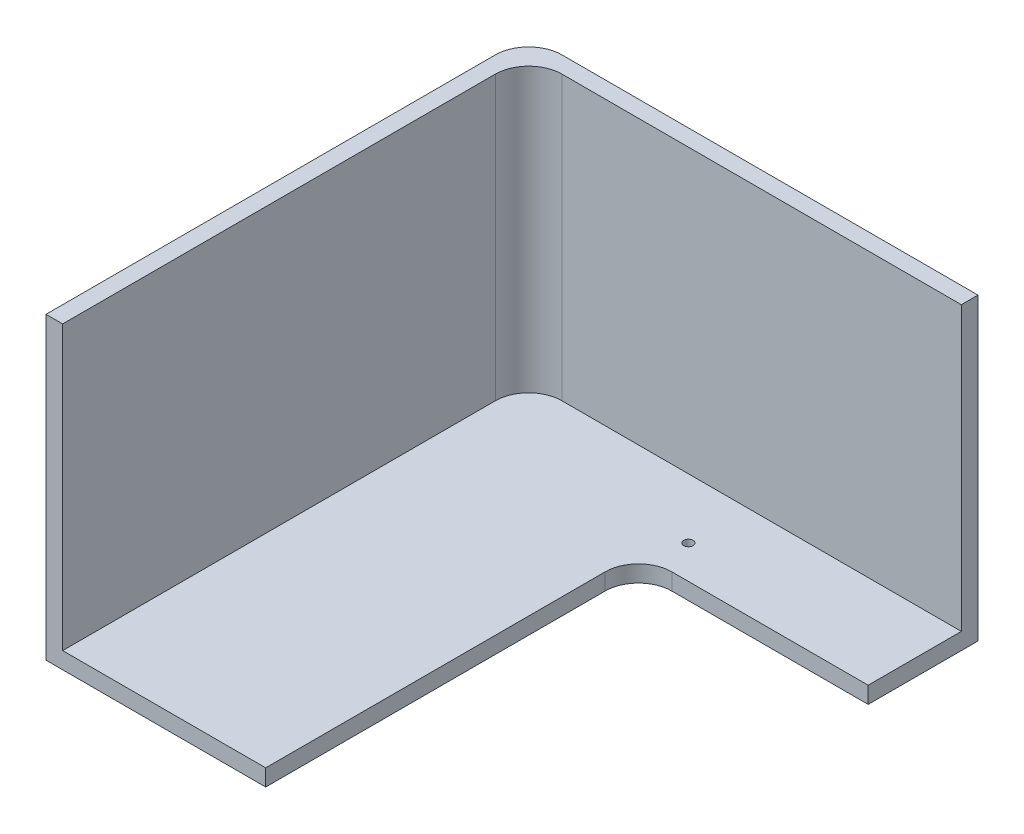
SolidWorks part; units mm, degrees
ref_plane "前视基准面" through (0, 0, 0) normal (0, 0, 1) x (1, 0, 0)
ref_plane "上视基准面" through (0, 0, 0) normal (0, 1, 0) x (1, 0, 0)
ref_plane "右视基准面" through (0, 0, 0) normal (1, 0, 0) x (0, 0, -1)
other "Configuration Table"
sketch "草图1" plane through (0, 0, 0) normal (0, 1, 0) x (1, 0, 0)
  line L1 (0, 0) -> (-135, 0)
  line L2 (0, 0) -> (0, -145)
  line L3 (0, -145) -> (-135, -145)
  line L4 (-135, 0) -> (-135, -145)
  dimension "D1" = 135
  dimension "D2" = 145
extrude "凸台-拉伸1" add sketch "草图1" along normal blind 90
sketch "草图2" plane through (0, 90, 0) normal (0, 1, 0) x (1, 0, 0)
  line L0 (0, -145) -> (0, 0) construction
  line L1 (0, -5) -> (-130, -5)
  line L2 (0, -5) -> (0, -145)
  line L3 (0, -145) -> (-130, -145)
  line L4 (-130, -5) -> (-130, -145)
  line L5 (-135, -145) -> (0, -145) construction
  line L6 (-135, 0) -> (-135, -145) construction
  line L7 (0, 0) -> (-135, 0) construction
  dimension "D1" = 5
  dimension "D2" = 5
extrude "切除-拉伸1" cut sketch "草图2" against normal offset from surface (85 mm away) 5 up to face at (-67.5, 0, 72.5)
sketch "草图3" plane through (0, 5, 0) normal (0, 1, 0) x (1, 0, 0)
  line L0 (0, -145) -> (0, -5) construction
  line L1 (0, -33) -> (-69, -33)
  line L2 (0, -33) -> (0, -145)
  line L3 (0, -145) -> (-69, -145)
  line L4 (-69, -33) -> (-69, -145)
  line L6 (-130, -145) -> (0, -145) construction
  dimension "D1" = 112
  dimension "D2" = 69
extrude "切除-拉伸2" cut sketch "草图3" against normal up to surface (5 mm away) up to face at (-67.5, 0, 72.5)
sketch "草图4" plane through (0, 5, 0) normal (0, 1, 0) x (1, 0, 0)
  line L0 (0, -33) -> (0, -5) construction
  line L1 (-130, -145) -> (-69, -145) construction
  circle A0 centre (-64, -23) radius 1.4
  dimension "D1" = 64
  dimension "D2" = 122
  dimension "D3" = 2.8
extrude "切除-拉伸3" cut sketch "草图4" against normal up to surface (5 mm away) up to face at (-68, 0, 59.3333)
fillet "圆角1" radius 10 3 edges at (-69, 2.5, 33) (-135, 45, 0) (-130, 47.5, 5)
